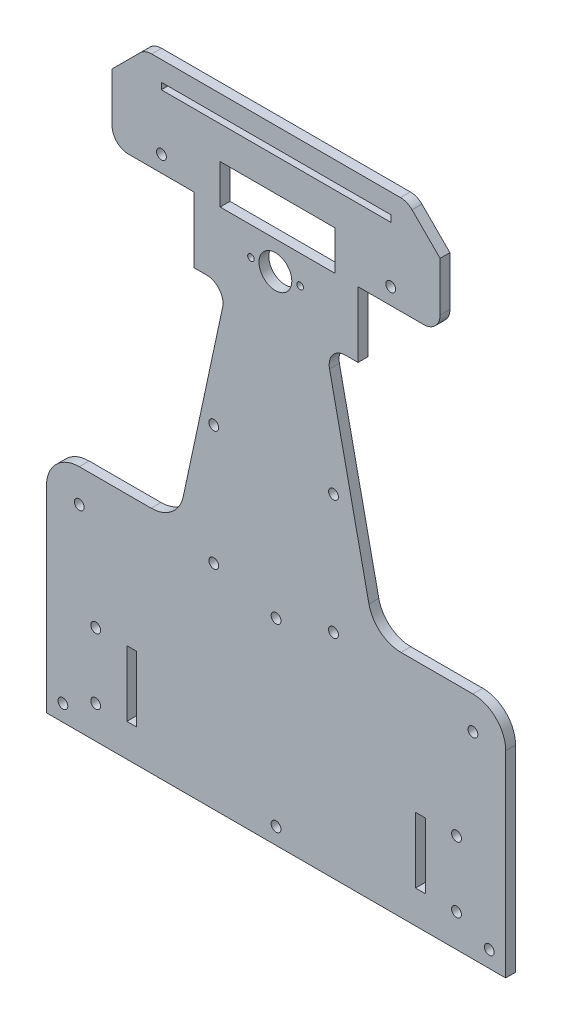
SolidWorks part; units mm, degrees
ref_plane "Alzado" through (0, 0, 0) normal (0, 0, 1) x (1, 0, 0)
ref_plane "Planta" through (0, 0, 0) normal (0, 1, 0) x (1, 0, 0)
ref_plane "Vista lateral" through (0, 0, 0) normal (1, 0, 0) x (0, 0, -1)
sketch "Croquis1" plane through (0, 0, 0) normal (0, 0, 1) x (1, 0, 0)
  line L0 (70, 0) -> (-70, 0)
  line L1 (-70, 0) -> (-70, 70)
  line L2 (70, 0) -> (70, 70)
  line L3 (-70, 70) -> (-30, 70)
  line L4 (70, 70) -> (30, 70)
  line L5 (-25, 140) -> (-25, 160)
  line L6 (-30, 70) -> (-15, 140)
  line L7 (15, 140) -> (25, 140)
  line L8 (-15, 140) -> (-25, 140)
  line L9 (25, 160) -> (50, 160)
  line L10 (-25, 160) -> (-50, 160)
  line L11 (30, 70) -> (15, 140)
  line L12 (25, 140) -> (25, 160)
  line L13 (-50, 160) -> (-50, 190)
  line L14 (50, 160) -> (50, 190)
  line L15 (50, 190) -> (-50, 190)
  point P4 (0, 0)
  dimension "D1" = 70
  dimension "D2" = 40
  dimension "D3" = 140
  dimension "D4" = 40
  dimension "D5" = 10
  dimension "D6" = 10
  dimension "D7" = 20
  dimension "D8" = 20
  dimension "D9" = 50
  dimension "D10" = 25
  dimension "D11" = 25
  dimension "D12" = 30
  dimension "D13" = 100
extrude "Saliente-Extruir1" add sketch "Croquis1" along normal blind 3
fillet "Redondeo1" radius 5 4 edges at (-50, 160, 1.5) (50, 160, 1.5) (15, 140, 1.5) (-15, 140, 1.5)
fillet "Redondeo2" radius 10 4 edges at (-70, 70, 1.5) (70, 70, 1.5) (30, 70, 1.5) (-30, 70, 1.5)
sketch "Croquis2" plane through (0, 0, 3) normal (0, 0, 1) x (1, 0, 0)
  line L0 (-70, 0) -> (70, 0) construction
  line L1 (-70, 60) -> (-70, 0) construction
  line L2 (70, 0) -> (70, 60) construction
  line L3 (25, 160) -> (45, 160) construction
  line L4 (-17.05, 160.017) -> (17.95, 160.017)
  line L10 (17.95, 172.017) -> (17.95, 160.017)
  line L11 (17.95, 172.017) -> (-17.05, 172.017)
  line L14 (50, 165) -> (50, 190) construction
  line L23 (-35, 182) -> (-35, 184)
  line L24 (-35, 184) -> (35, 184)
  line L25 (-50, 190) -> (-50, 165) construction
  line L26 (-38.0842, 70) -> (-60, 70) construction
  line L27 (-35, 182) -> (35, 182)
  line L28 (35, 184) -> (35, 182)
  line L29 (60, 70) -> (38.0842, 70) construction
  line L30 (0, 0) -> (0, 209.7364) construction
  line L31 (-45.5, 30) -> (-45.5, 10)
  line L32 (-45.5, 10) -> (-42.5, 10)
  line L33 (-42.5, 10) -> (-42.5, 30)
  line L34 (-42.5, 30) -> (-45.5, 30)
  line L35 (45.5, 30) -> (42.5, 30)
  line L36 (42.5, 30) -> (42.5, 10)
  line L37 (42.5, 10) -> (45.5, 10)
  line L38 (45.5, 10) -> (45.5, 30)
  line L40 (-17.05, 172.017) -> (-17.05, 160.017)
  circle A0 centre (-55, 10) radius 1.5
  circle A1 centre (-55, 30) radius 1.5
  circle A2 centre (55, 10) radius 1.5
  circle A3 centre (55, 30) radius 1.5
  circle A5 centre (34.95, 165) radius 1.5
  circle A6 centre (-0.2054, 151.3869) radius 5
  circle A7 centre (-7.6554, 151.3869) radius 1
  circle A8 centre (7.3446, 151.3869) radius 1
  circle A9 centre (-65, 5) radius 1.5
  circle A10 centre (-60, 60) radius 1.5
  circle A11 centre (65, 5) radius 1.5
  circle A12 centre (60, 60) radius 1.5
  circle A13 centre (0, 5) radius 1.5
  circle A14 centre (0, 60) radius 1.5
  circle A15 centre (-19, 65) radius 1.5
  circle A16 centre (17.5, 65) radius 1.5
  circle A18 centre (-19, 101.5) radius 1.5
  circle A19 centre (17.5, 101.5) radius 1.5
  circle A20 centre (-34.95, 165) radius 1.5
  dimension "D2" = 3
  dimension "D3" = 3
  dimension "D7" = 3
  dimension "D8" = 3
  dimension "D11" = 34.95
  dimension "D15" = 10
  dimension "D18" = 2
  dimension "D19" = 2
  dimension "D28" = 3
  dimension "D33" = 3
  dimension "D36" = 3
  dimension "D39" = 3
  dimension "D40" = 3
  dimension "D42" = 3
  dimension "D44" = 5
  dimension "D45" = 3
  dimension "D48" = 3
  dimension "D49" = 3
  dimension "D50" = 3
  dimension "D53" = 36.5
  dimension "D63" = 3
  dimension "D64" = 3
  dimension "D1" = 20
  dimension "D4" = 10
  dimension "D5" = 15
  dimension "D6" = 20
  dimension "D9" = 15
  dimension "D10" = 10
  dimension "D12" = 5
  dimension "D13" = 69.9
  dimension "D14" = 34.95
  dimension "D16" = 15.05
  dimension "D17" = 15.05
  dimension "D20" = 7.55
  dimension "D21" = 15
  dimension "D22" = 17
  dimension "D23" = 2
  dimension "D24" = 15
  dimension "D25" = 15
  dimension "D26" = 15
  dimension "D27" = 15
  dimension "D29" = 5
  dimension "D30" = 5
  dimension "D31" = 10
  dimension "D32" = 10
  dimension "D34" = 5
  dimension "D35" = 5
  dimension "D37" = 10
  dimension "D38" = 10
  dimension "D41" = 5
  dimension "D43" = 55
  dimension "D46" = 5
  dimension "D47" = 52.5
  dimension "D51" = 36.5
  dimension "D52" = 36.5
  dimension "D54" = 36.5
  dimension "D55" = 3
  dimension "D56" = 12.5
  dimension "D57" = 20
  dimension "D58" = 20
  dimension "D59" = 3
  dimension "D60" = 12.5
  dimension "D61" = 35
  dimension "D62" = 12
extrude "Cortar-Extruir1" cut sketch "Croquis2" against normal blind 10
chamfer "Chaflán1" distance 10 angle 45 2 edges at (50, 190, 1.5) (-50, 190, 1.5)
fillet "Redondeo3" radius 5 2 edges at (40, 190, 1.5) (-40, 190, 1.5)
